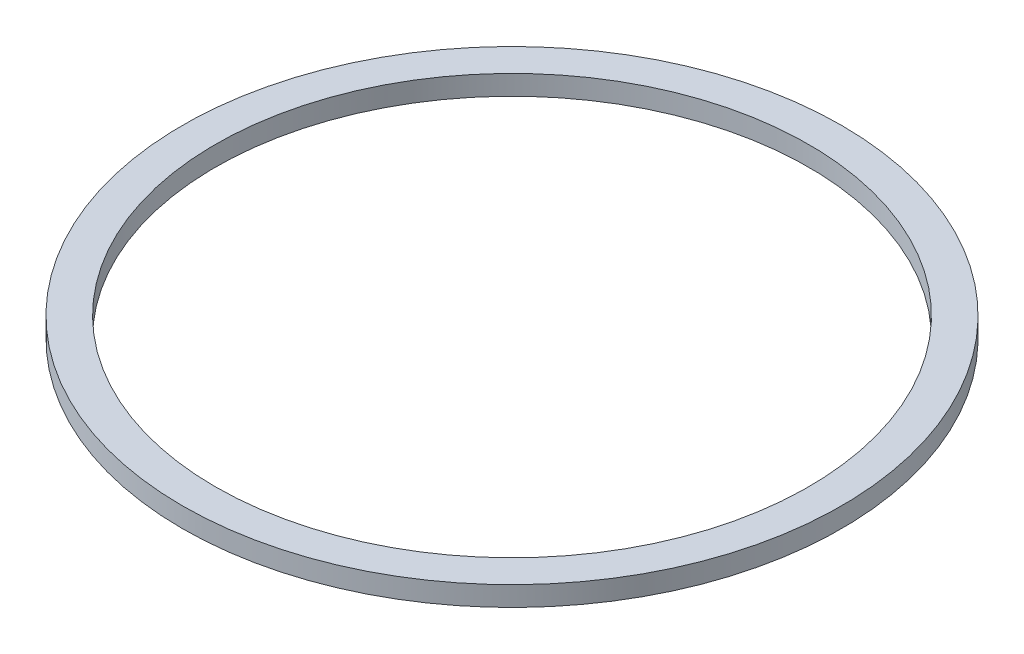
SolidWorks part; units mm, degrees
material "EPDM 60 Durometre"
ref_plane "Ön Düzlem" through (0, 0, 0) normal (0, 0, 1) x (1, 0, 0)
ref_plane "Üst Düzlem" through (0, 0, 0) normal (0, 1, 0) x (1, 0, 0)
ref_plane "Sağ Düzlem" through (0, 0, 0) normal (1, 0, 0) x (0, 0, -1)
sketch "Çizim1" plane through (0, 0, 0) normal (0, 1, 0) x (1, 0, 0)
  circle A0 centre (0, 0) radius 50
  circle A1 centre (0, 0) radius 45
  dimension "D1" = 100
  dimension "D2" = 90
extrude "Yükseklik-Ekstrüzyon1" add sketch "Çizim1" along normal blind 3
